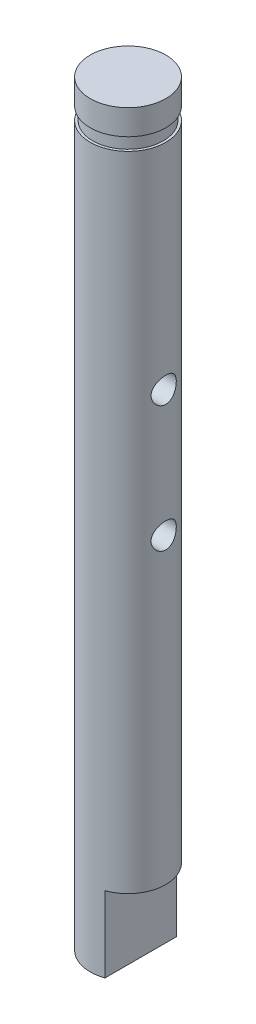
SolidWorks part; units mm, degrees
ref_plane "Alzado" through (0, 0, 0) normal (0, 0, 1) x (1, 0, 0)
ref_plane "Planta" through (0, 0, 0) normal (0, 1, 0) x (1, 0, 0)
ref_plane "Vista lateral" through (0, 0, 0) normal (1, 0, 0) x (0, 0, -1)
sketch "Croquis1" plane through (0, 0, 0) normal (0, 1, 0) x (1, 0, 0)
  circle A0 centre (0, 0) radius 3
  dimension "D1" = 6
extrude "Saliente-Extruir1" add sketch "Croquis1" along normal blind 60
ref_axis "Eje1" through (0, 60, 0) along (0, -1, 0)
sketch "Croquis2" plane through (0, 0, 0) normal (0, 0, 1) x (1, 0, 0)
  line L0 (3, 0) -> (3, 60) construction
  line L1 (2.8, 58) -> (8.3312, 58)
  line L2 (2.8, 58) -> (2.8, 57)
  line L3 (2.8, 57) -> (8.3312, 57)
  line L4 (8.3312, 58) -> (8.3312, 57)
  line L5 (3, 60) -> (-3, 60) construction
  dimension "D1" = 1
  dimension "D2" = 0.2
  dimension "D3" = 2
revolve "Cortar-Revolución1" cut sketch "Croquis2" angle 360 about axis through (0, 60, 0) along (0, -1, 0)
sketch "Croquis3" plane through (0, 0, 0) normal (1, 0, 0) x (0, 0, -1)
  line L0 (0, 60) -> (0, 0) construction
  line L2 (3, 60) -> (-3, 60) construction
  circle A0 centre (0, 40) radius 1
  circle A1 centre (0, 30) radius 1
  dimension "D1" = 2
  dimension "D2" = 10
  dimension "D3" = 20
extrude "Cortar-Extruir1" cut sketch "Croquis3" against normal through all both and the other way through all
sketch "Croquis4" plane through (0, 0, 0) normal (0, -1, 0) x (1, 0, 0)
  line L0 (1, 2.8284) -> (1, -2.8284)
  circle A0 centre (0, 0) radius 3 construction
  arc A1 (1, -2.8284) -> (1, 2.8284) centre (0, 0) ccw
  dimension "D1" = 2
extrude "Cortar-Extruir2" cut sketch "Croquis4" against normal blind 6
